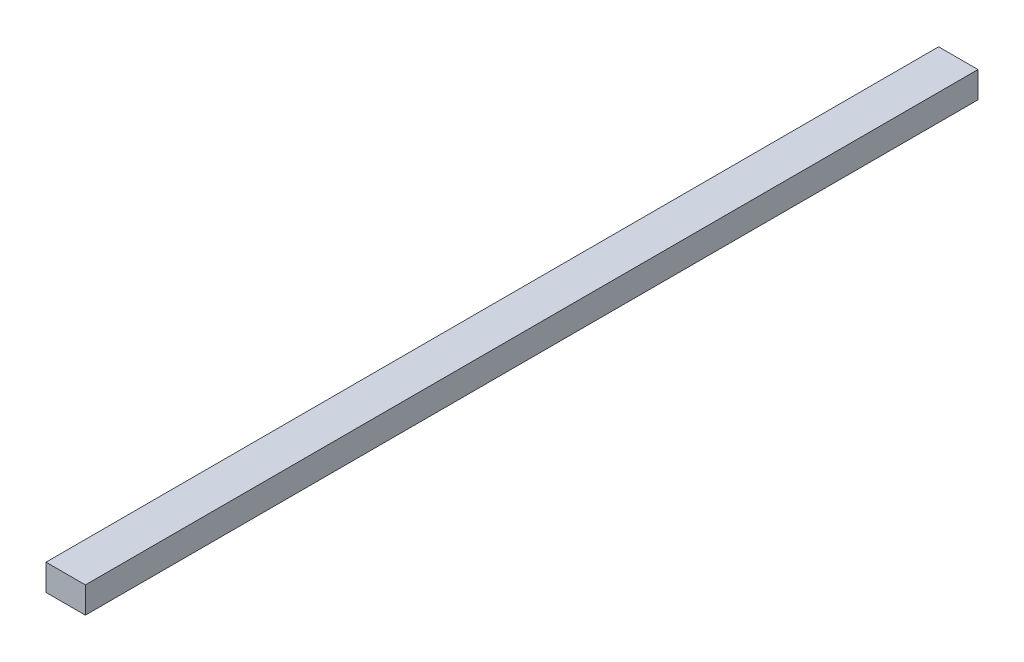
SolidWorks part; units mm, degrees
ref_plane "Front Plane" through (0, 0, 0) normal (0, 0, 1) x (1, 0, 0)
ref_plane "Top Plane" through (0, 0, 0) normal (0, 1, 0) x (1, 0, 0)
ref_plane "Right Plane" through (0, 0, 0) normal (1, 0, 0) x (0, 0, -1)
other "Configuration Table"
sketch "Sketch1" plane through (0, 0, 0) normal (0, 0, 1) x (1, 0, 0)
  line L1 (35, 0) -> (65, 0)
  line L2 (35, 0) -> (35, 20)
  line L3 (35, 20) -> (65, 20)
  line L4 (65, 0) -> (65, 20)
extrude "KAP_kizak_sag_30x20_1" add sketch "Sketch1" against normal blind 680 from offset 20 separate body
